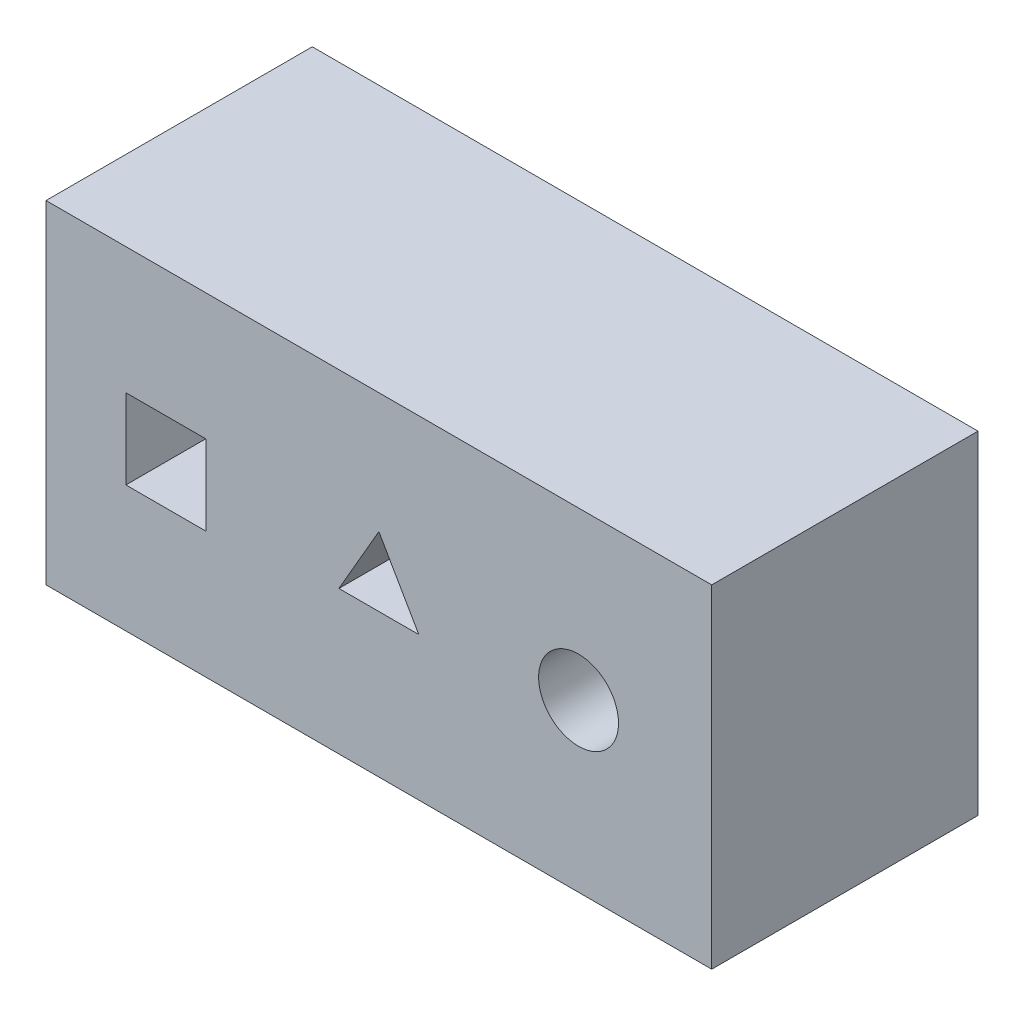
SolidWorks part; units mm, degrees
ref_plane "Front Plane" through (0, 0, 0) normal (0, 0, 1) x (1, 0, 0)
ref_plane "Top Plane" through (0, 0, 0) normal (0, 1, 0) x (1, 0, 0)
ref_plane "Right Plane" through (0, 0, 0) normal (1, 0, 0) x (0, 0, -1)
sketch "Sketch1" plane through (0, 0, 0) normal (0, 0, 1) x (1, 0, 0)
  line L1 (125, -62.5) -> (-125, -62.5)
  line L2 (125, -62.5) -> (125, 62.5)
  line L3 (125, 62.5) -> (-125, 62.5)
  line L4 (-125, -62.5) -> (-125, 62.5)
  line L5 (125, -62.5) -> (-125, 62.5) construction
  line L6 (125, 62.5) -> (-125, -62.5) construction
  line L7 (115, -57.5) -> (-115, -57.5)
  line L8 (115, -57.5) -> (115, 57.5)
  line L9 (115, 57.5) -> (-115, 57.5)
  line L10 (-115, -57.5) -> (-115, 57.5)
  line L11 (115, -57.5) -> (-115, 57.5) construction
  line L12 (115, 57.5) -> (-115, -57.5) construction
  point P0 (0, 0)
  point P6 (0, 0)
  dimension "D1" = 250
  dimension "D2" = 125
  dimension "D3" = 230
extrude "Boss-Extrude1" add sketch "Sketch1" along normal blind 100
sketch "Sketch2" plane through (0, 0, 0) normal (0, 0, -1) x (-1, 0, 0)
  line L1 (125, 62.5) -> (-125, 62.5)
  line L2 (125, 62.5) -> (125, -62.5)
  line L3 (125, -62.5) -> (-125, -62.5)
  line L4 (-125, 62.5) -> (-125, -62.5)
sketch "Sketch3" plane through (0, 0, 100) normal (0, 0, 1) x (1, 0, 0)
  line L0 (-125, 0) -> (125, 0) construction
  line L1 (-125, 62.5) -> (125, 62.5)
  line L2 (-125, 62.5) -> (-125, -62.5)
  line L3 (-125, -62.5) -> (125, -62.5)
  line L4 (125, 62.5) -> (125, -62.5)
  line L5 (0, 62.5) -> (0, -62.5) construction
  line L6 (-15, -8.6603) -> (0, 17.3205)
  line L7 (-95, 15) -> (-65, 15)
  line L8 (-95, 15) -> (-95, -15)
  line L9 (-95, -15) -> (-65, -15)
  line L10 (-65, 15) -> (-65, -15)
  line L11 (-95, 15) -> (-65, -15) construction
  line L12 (-95, -15) -> (-65, 15) construction
  line L14 (-1.3522, 0) -> (0, -1.3522)
  line L18 (0, 17.3205) -> (15, -8.6603)
  line L19 (15, -8.6603) -> (-15, -8.6603)
  line L20 (-15, -8.6603) -> (7.5, 4.3301) construction
  line L21 (15, -8.6603) -> (-7.5, 4.3301) construction
  line L22 (0, 17.3205) -> (0, 0) construction
  circle A0 centre (75, 0) radius 15
  point P10 (-80, 0)
  point P20 (0, 0)
  point P27 (7.7505, -5.3087)
  point P28 (0, 0)
  line M21 (-125, 62.5) -> (-125, -62.5)
  line M22 (-125, -62.5) -> (125, -62.5)
  line M23 (125, -62.5) -> (125, 62.5)
  line M24 (125, 62.5) -> (-125, 62.5)
  line M25 (115, -57.5) -> (-115, -57.5)
  line M26 (-115, -57.5) -> (-115, 57.5)
  line M27 (-115, 57.5) -> (115, 57.5)
  line M28 (115, 57.5) -> (115, -57.5)
  dimension "D2" = 50
  dimension "cylinder" = 30
  dimension "D1" = 30
  dimension "square2" = 30
  dimension "square" = 30
  dimension "triangle3" = 30
  dimension "triangle2" = 30
  dimension "triangle" = 30
extrude "Boss-Extrude4" add sketch "Sketch3" against normal up to surface (100 mm away) contours A0 L7 L10 L9 L8 L18 L19 L6 M25 M28 M27 M26 | M24 M21 M22 M23 M28 M25 M26 M27 up to face at (0, 0, 0)
